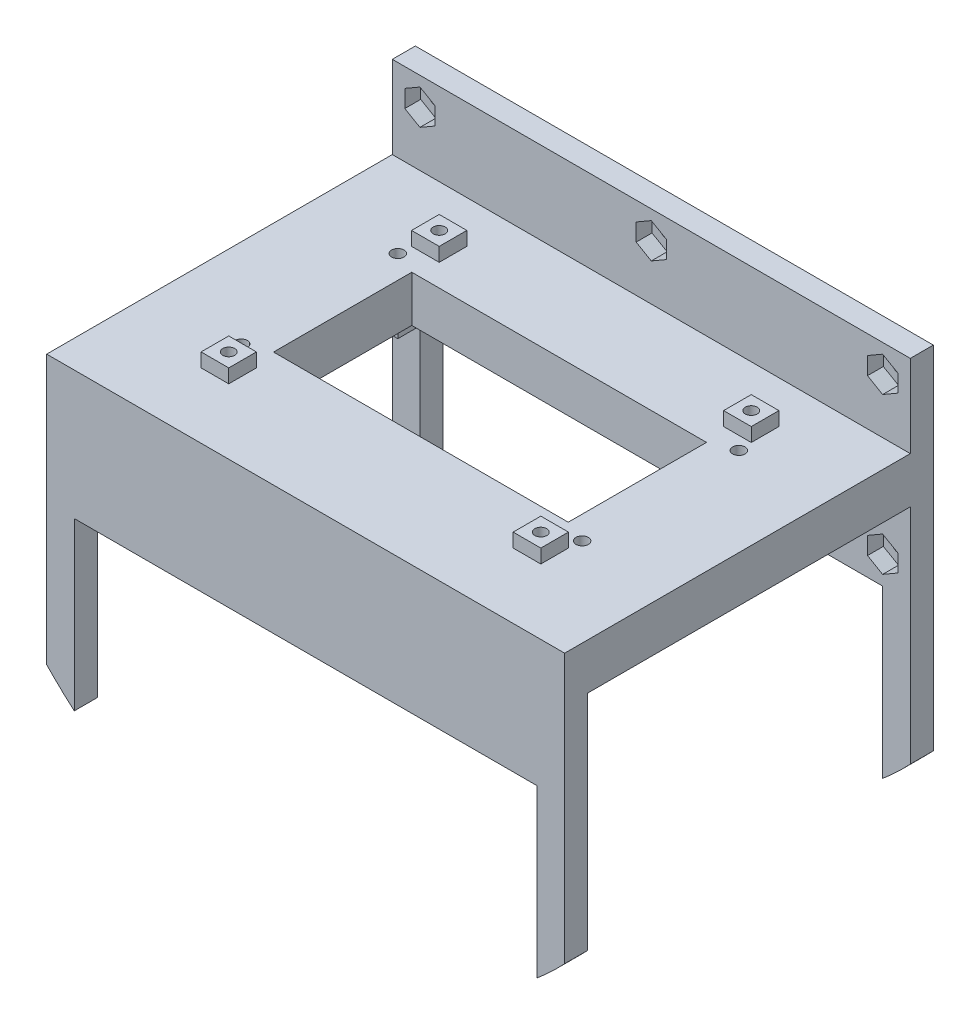
SolidWorks part; units mm, degrees
ref_plane "Front Plane" through (0, 0, 0) normal (0, 0, 1) x (1, 0, 0)
ref_plane "Top Plane" through (0, 0, 0) normal (0, 1, 0) x (1, 0, 0)
ref_plane "Right Plane" through (0, 0, 0) normal (1, 0, 0) x (0, 0, -1)
sketch "Sketch1" plane through (0, 0, 0) normal (0, 0, 1) x (1, 0, 0)
  line L0 (-71.374, -29.0845) -> (-71.374, -67.7734)
  line L1 (-63.754, -21.4645) -> (63.754, -21.4645) construction
  line L2 (-63.754, -21.4645) -> (-63.754, 21.4645) construction
  line L3 (-63.754, 21.4645) -> (63.754, 21.4645) construction
  line L4 (63.754, -21.4645) -> (63.754, 21.4645) construction
  line L5 (-63.754, -21.4645) -> (63.754, 21.4645) construction
  line L6 (-63.754, 21.4645) -> (63.754, -21.4645) construction
  line L7 (-63.754, -29.0845) -> (63.754, -29.0845)
  line L8 (-71.374, -29.0845) -> (-71.374, 29.0845)
  line L9 (-71.374, 29.0845) -> (71.374, 29.0845)
  line L10 (71.374, -29.0845) -> (71.374, 29.0845)
  line L11 (-71.374, -29.0845) -> (71.374, 29.0845) construction
  line L12 (-71.374, 29.0845) -> (71.374, -29.0845) construction
  line L13 (-63.754, -29.0845) -> (-63.754, -74.9861)
  line L14 (71.374, -29.0845) -> (71.374, -67.7734)
  line L15 (63.754, -29.0845) -> (63.754, -74.9861)
  circle A0 centre (-63.754, 21.4645) radius 1.8986
  circle A1 centre (0, 21.4645) radius 1.8986
  circle A2 centre (63.754, 21.4645) radius 1.8987
  circle A3 centre (63.754, -21.4645) radius 1.8987
  circle A4 centre (0, -21.4645) radius 1.8986
  circle A5 centre (-63.754, -21.4645) radius 1.8986
  circle A6 centre (0, 0) radius 98.425 construction
  arc A7 (-71.374, -67.7734) -> (-63.754, -74.9861) centre (0, 0) ccw
  arc A8 (71.374, -67.7734) -> (63.754, -74.9861) centre (0, 0) cw
  point P0 (0, 0)
  dimension "D1" = 3.7973
  dimension "D4" = 196.85
  dimension "D2" = 127.508
  dimension "D3" = 42.929
  dimension "D5" = 7.62
  dimension "D6" = 7.62
  dimension "D7" = 7.62
  dimension "D8" = 7.62
extrude "Boss-Extrude1" add sketch "Sketch1" along normal blind 6.35
sketch "Sketch2" plane through (0, 0, 6.35) normal (0, 0, 1) x (1, 0, 0)
  line L0 (71.374, -67.7734) -> (71.374, 29.0845) construction
  line L1 (-71.374, -6.35) -> (71.374, -6.35)
  line L2 (-71.374, -6.35) -> (-71.374, 6.35)
  line L3 (-71.374, 6.35) -> (71.374, 6.35)
  line L4 (71.374, -6.35) -> (71.374, 6.35)
  line L5 (-71.374, -6.35) -> (71.374, 6.35) construction
  line L6 (-71.374, 6.35) -> (71.374, -6.35) construction
  point P0 (0, 0)
  dimension "D1" = 12.7
extrude "Boss-Extrude2" add sketch "Sketch2" along normal blind 88.9
sketch "Sketch3" plane through (0, -6.35, 0) normal (0, -1, 0) x (1, 0, 0)
  line L0 (-63.754, 6.35) -> (63.754, 6.35) construction
  line L1 (-46.99, 29.21) -> (46.99, 29.21) construction
  line L2 (-46.99, 29.21) -> (-46.99, 72.39) construction
  line L3 (-46.99, 72.39) -> (46.99, 72.39) construction
  line L4 (46.99, 29.21) -> (46.99, 72.39) construction
  line L5 (-46.99, 29.21) -> (46.99, 72.39) construction
  line L6 (-46.99, 72.39) -> (46.99, 29.21) construction
  line L14 (-50.8, 68.58) -> (-43.18, 68.58)
  line L15 (-50.8, 68.58) -> (-50.8, 76.2)
  line L16 (-50.8, 76.2) -> (-43.18, 76.2)
  line L17 (-43.18, 68.58) -> (-43.18, 76.2)
  line L18 (-50.8, 68.58) -> (-43.18, 76.2) construction
  line L19 (-50.8, 76.2) -> (-43.18, 68.58) construction
  line L20 (43.18, 68.58) -> (50.8, 68.58)
  line L21 (43.18, 68.58) -> (43.18, 76.2)
  line L22 (43.18, 76.2) -> (50.8, 76.2)
  line L23 (50.8, 68.58) -> (50.8, 76.2)
  line L24 (43.18, 68.58) -> (50.8, 76.2) construction
  line L25 (43.18, 76.2) -> (50.8, 68.58) construction
  line L26 (43.18, 25.4) -> (50.8, 25.4)
  line L27 (43.18, 25.4) -> (43.18, 33.02)
  line L28 (43.18, 33.02) -> (50.8, 33.02)
  line L29 (50.8, 25.4) -> (50.8, 33.02)
  line L30 (43.18, 25.4) -> (50.8, 33.02) construction
  line L31 (43.18, 33.02) -> (50.8, 25.4) construction
  line L32 (-50.8, 25.4) -> (-43.18, 25.4)
  line L33 (-50.8, 25.4) -> (-50.8, 33.02)
  line L34 (-50.8, 33.02) -> (-43.18, 33.02)
  line L35 (-43.18, 25.4) -> (-43.18, 33.02)
  line L36 (-50.8, 25.4) -> (-43.18, 33.02) construction
  line L37 (-50.8, 33.02) -> (-43.18, 25.4) construction
  circle A0 centre (-46.99, 72.39) radius 1.7
  circle A1 centre (46.99, 72.39) radius 1.7
  circle A2 centre (46.99, 29.21) radius 1.7
  circle A3 centre (-46.99, 29.21) radius 1.7
  point P0 (0, 50.8)
  point P12 (0, 50.8)
  dimension "D4" = 3.4
  dimension "D1" = 44.45
  dimension "D2" = 43.18
  dimension "D3" = 93.98
  dimension "D5" = 3.81
extrude "Boss-Extrude3" add sketch "Sketch3" along normal blind 3.81
sketch "Sketch4" plane through (0, -6.35, 0) normal (0, -1, 0) x (1, 0, 0)
  line L1 (-40.6106, 31.75) -> (40.6106, 31.75)
  line L2 (-40.6106, 31.75) -> (-40.6106, 69.85)
  line L3 (-40.6106, 69.85) -> (40.6106, 69.85)
  line L4 (40.6106, 31.75) -> (40.6106, 69.85)
  line L5 (-40.6106, 31.75) -> (40.6106, 69.85) construction
  line L6 (-40.6106, 69.85) -> (40.6106, 31.75) construction
  circle A0 centre (-46.99, 29.21) radius 1.7 construction
  circle A1 centre (-46.99, 29.21) radius 1.7
  circle A2 centre (-46.99, 72.39) radius 1.7 construction
  circle A3 centre (-46.99, 72.39) radius 1.7
  circle A4 centre (46.99, 29.21) radius 1.7 construction
  circle A5 centre (46.99, 72.39) radius 1.7 construction
  circle A6 centre (46.99, 29.21) radius 1.7
  circle A7 centre (46.99, 72.39) radius 1.7
  point P0 (0, 50.8)
  dimension "D1" = 38.1
  dimension "D2" = 81.2213
extrude "Cut-Extrude2" cut sketch "Sketch4" against normal up to next
sketch "Sketch5" plane through (0, 6.35, 0) normal (0, 1, 0) x (1, 0, 0)
  line L0 (-46.99, -29.21) -> (46.99, -72.39) construction
  line L1 (-43, -79.8) -> (43, -79.8) construction
  line L2 (-43, -79.8) -> (-43, -21.8) construction
  line L3 (-43, -21.8) -> (43, -21.8) construction
  line L4 (43, -79.8) -> (43, -21.8) construction
  line L5 (-43, -79.8) -> (43, -21.8) construction
  line L6 (-43, -21.8) -> (43, -79.8) construction
  line L9 (-46.81, -25.61) -> (-39.19, -25.61)
  line L10 (-46.81, -25.61) -> (-46.81, -17.99)
  line L11 (-46.81, -17.99) -> (-39.19, -17.99)
  line L12 (-39.19, -25.61) -> (-39.19, -17.99)
  line L13 (-46.81, -25.61) -> (-39.19, -17.99) construction
  line L14 (-46.81, -17.99) -> (-39.19, -25.61) construction
  line L15 (39.19, -25.61) -> (46.81, -25.61)
  line L16 (39.19, -25.61) -> (39.19, -17.99)
  line L17 (39.19, -17.99) -> (46.81, -17.99)
  line L18 (46.81, -25.61) -> (46.81, -17.99)
  line L19 (39.19, -25.61) -> (46.81, -17.99) construction
  line L20 (39.19, -17.99) -> (46.81, -25.61) construction
  line L21 (39.19, -83.61) -> (46.81, -83.61)
  line L22 (39.19, -83.61) -> (39.19, -75.99)
  line L23 (39.19, -75.99) -> (46.81, -75.99)
  line L24 (46.81, -83.61) -> (46.81, -75.99)
  line L25 (39.19, -83.61) -> (46.81, -75.99) construction
  line L26 (39.19, -75.99) -> (46.81, -83.61) construction
  line L27 (-46.81, -83.61) -> (-39.19, -83.61)
  line L28 (-46.81, -83.61) -> (-46.81, -75.99)
  line L29 (-46.81, -75.99) -> (-39.19, -75.99)
  line L30 (-39.19, -83.61) -> (-39.19, -75.99)
  line L31 (-46.81, -83.61) -> (-39.19, -75.99) construction
  line L32 (-46.81, -75.99) -> (-39.19, -83.61) construction
  circle A0 centre (-43, -21.8) radius 1.65
  circle A1 centre (43, -21.8) radius 1.65
  circle A2 centre (43, -79.8) radius 1.65
  circle A3 centre (-43, -79.8) radius 1.65
  point P0 (0, -50.8)
  dimension "D3" = 3.3
  dimension "D1" = 86
  dimension "D2" = 58
  dimension "D4" = 3.81
extrude "Boss-Extrude4" add sketch "Sketch5" along normal blind 3.81
sketch "Sketch6" plane through (0, 0, 95.25) normal (0, 0, 1) x (1, 0, 0)
  line L0 (-71.374, 6.35) -> (71.374, 6.35)
  line L1 (71.374, -6.35) -> (71.374, 6.35) construction
  line L2 (71.374, -67.7734) -> (71.374, -6.35) construction
  line L3 (63.754, -29.0845) -> (63.754, -74.9861) construction
  line L4 (-63.754, -29.0845) -> (63.754, -29.0845) construction
  line L5 (-63.754, -74.9861) -> (-63.754, -29.0845) construction
  line L6 (-71.374, -6.35) -> (-71.374, -67.7734) construction
  line L7 (-71.374, 6.35) -> (-71.374, -6.35) construction
  line L8 (71.374, -6.35) -> (71.374, 6.35)
  line L9 (71.374, -67.7734) -> (71.374, -6.35)
  line L10 (63.754, -29.0845) -> (63.754, -74.9861)
  line L11 (-63.754, -29.0845) -> (63.754, -29.0845)
  line L12 (-63.754, -74.9861) -> (-63.754, -29.0845)
  line L13 (-71.374, -6.35) -> (-71.374, -67.7734)
  line L14 (-71.374, 6.35) -> (-71.374, -6.35)
  arc A0 (63.754, -74.9861) -> (71.374, -67.7734) centre (0, 0) ccw construction
  arc A1 (-71.374, -67.7734) -> (-63.754, -74.9861) centre (0, 0) ccw construction
  arc A2 (63.754, -74.9861) -> (71.374, -67.7734) centre (0, 0) ccw
  arc A3 (-71.374, -67.7734) -> (-63.754, -74.9861) centre (0, 0) ccw
extrude "Boss-Extrude5" add sketch "Sketch6" along normal blind 6.35
sketch "Sketch9" plane through (0, 6.35, 0) normal (0, 1, 0) x (1, 0, 0)
  circle A0 centre (-43, -21.8) radius 1.65 construction
  circle A1 centre (-43, -21.8) radius 1.65
  circle A2 centre (43, -21.8) radius 1.65 construction
  circle A3 centre (43, -21.8) radius 1.65
  circle A4 centre (-43, -79.8) radius 1.65 construction
  circle A5 centre (-43, -79.8) radius 1.65
  circle A6 centre (43, -79.8) radius 1.65 construction
  circle A7 centre (43, -79.8) radius 1.65
extrude "Cut-Extrude3" cut sketch "Sketch9" against normal through all both and the other way through all
sketch "Sketch10" plane through (0, 0, 6.35) normal (0, 0, 1) x (1, 0, 0)
  line L0 (4.1687, 19.0577) -> (4.1687, 23.8713)
  line L1 (3.9687, 23.7559) -> (0, 26.0472) construction
  line L2 (0, 26.0472) -> (-3.9688, 23.7559) construction
  line L3 (-3.9688, 23.7559) -> (-3.9688, 19.1731) construction
  line L4 (-3.9688, 19.1731) -> (0, 16.8818) construction
  line L5 (0, 16.8818) -> (3.9687, 19.1731) construction
  line L6 (3.9687, 19.1731) -> (3.9687, 23.7559) construction
  line L7 (4.1687, 23.8713) -> (0, 26.2782)
  line L8 (0, 26.2782) -> (-4.1688, 23.8713)
  line L9 (-4.1688, 23.8713) -> (-4.1688, 19.0577)
  line L10 (-4.1688, 19.0577) -> (0, 16.6508)
  line L11 (0, 16.6508) -> (4.1687, 19.0577)
  line L12 (-6.6664, 0) -> (37.6485, 0) construction
  line L13 (0, 13.3387) -> (0, -18.6551) construction
  line L14 (0, -16.6508) -> (4.1687, -19.0577)
  line L15 (-4.1688, -19.0577) -> (0, -16.6508)
  line L16 (-4.1688, -23.8713) -> (-4.1688, -19.0577)
  line L17 (0, -26.2782) -> (-4.1688, -23.8713)
  line L18 (4.1687, -23.8713) -> (0, -26.2782)
  line L19 (4.1687, -19.0577) -> (4.1687, -23.8713)
  line L20 (-63.754, 21.4645) -> (-63.754, -21.4645) construction
  line L21 (0, 0) -> (-63.754, 0) construction
  line L22 (-31.877, 0) -> (-31.877, 30.492) construction
  line L23 (-59.5852, -19.0577) -> (-63.754, -16.6508)
  line L24 (-59.5852, -23.8713) -> (-59.5852, -19.0577)
  line L25 (-63.754, -26.2782) -> (-59.5852, -23.8713)
  line L26 (-67.9227, -23.8713) -> (-63.754, -26.2782)
  line L27 (-67.9227, -19.0577) -> (-67.9227, -23.8713)
  line L28 (-63.754, -16.6508) -> (-67.9227, -19.0577)
  line L29 (-63.754, 16.6508) -> (-67.9227, 19.0577)
  line L30 (-59.5852, 19.0577) -> (-63.754, 16.6508)
  line L31 (-59.5852, 23.8713) -> (-59.5852, 19.0577)
  line L32 (-63.754, 26.2782) -> (-59.5852, 23.8713)
  line L33 (-67.9227, 23.8713) -> (-63.754, 26.2782)
  line L34 (-67.9227, 19.0577) -> (-67.9227, 23.8713)
  line L35 (59.5853, -23.8713) -> (59.5852, -19.0577)
  line L36 (63.754, -26.2782) -> (59.5853, -23.8713)
  line L37 (67.9228, -23.8713) -> (63.754, -26.2782)
  line L38 (67.9227, -19.0577) -> (67.9228, -23.8713)
  line L39 (63.754, -16.6508) -> (67.9227, -19.0577)
  line L40 (59.5852, -19.0577) -> (63.754, -16.6508)
  line L41 (59.5852, 19.0577) -> (63.754, 16.6508)
  line L42 (59.5852, 23.8713) -> (59.5852, 19.0577)
  line L43 (63.754, 26.2782) -> (59.5852, 23.8713)
  line L44 (67.9227, 23.8713) -> (63.754, 26.2782)
  line L45 (67.9227, 19.0577) -> (67.9227, 23.8713)
  line L46 (63.754, 16.6508) -> (67.9227, 19.0577)
  circle A0 centre (0, 21.4645) radius 3.9688 construction
  dimension "D1" = 7.9375
  dimension "D2" = 0.2
extrude "Cut-Extrude4" cut sketch "Sketch10" against normal blind 4.3656
